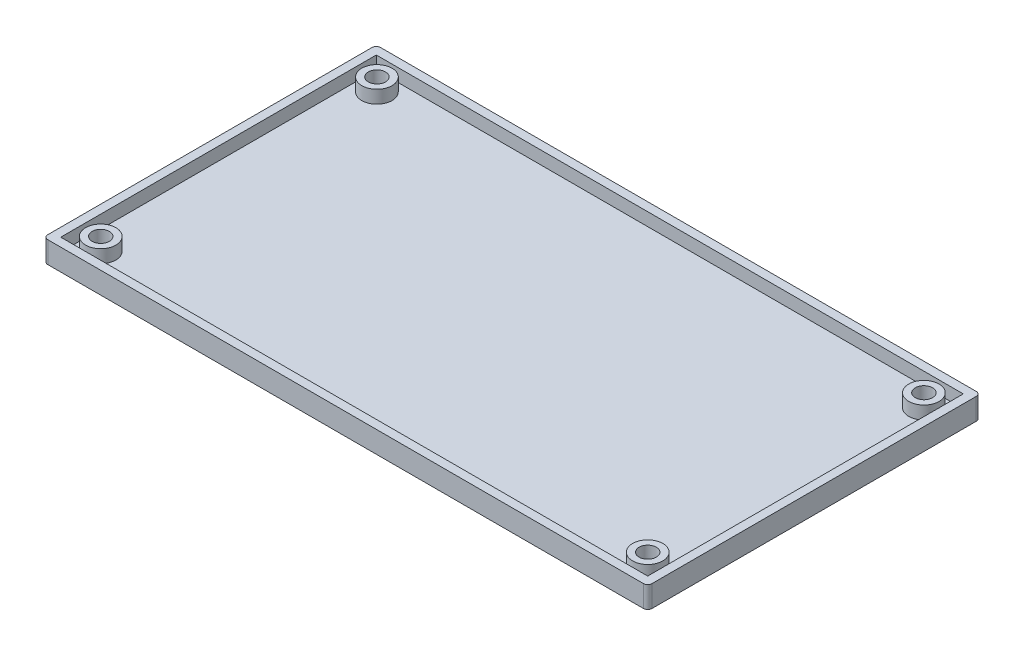
SolidWorks part; units mm, degrees
ref_plane "Front Plane" through (0, 0, 0) normal (0, 0, 1) x (1, 0, 0)
ref_plane "Top Plane" through (0, 0, 0) normal (0, 1, 0) x (1, 0, 0)
ref_plane "Right Plane" through (0, 0, 0) normal (1, 0, 0) x (0, 0, -1)
sketch "Sketch1" plane through (0, 0, 0) normal (0, 1, 0) x (1, 0, 0)
  line L0 (1.0429, 69.9365) -> (132.9972, 69.9365)
  line L1 (132.9972, 0.8484) -> (1.0429, 0.8484)
  line L2 (1.0429, 0.8484) -> (1.0429, 69.8095)
  line L3 (132.9972, 69.8095) -> (132.9972, 0.8484)
  line L4 (94.6421, 48.4741) -> (94.8961, 48.4741)
  line L5 (89.5621, 48.4741) -> (89.3081, 48.4741)
  line L6 (94.6421, 48.4741) -> (94.6421, 47.7121)
  line L7 (94.6421, 49.2361) -> (94.6421, 48.4741)
  line L8 (89.5621, 49.2361) -> (94.6421, 49.2361)
  line L9 (89.5621, 48.4741) -> (89.5621, 49.2361)
  line L10 (89.5621, 47.7121) -> (89.5621, 48.4741)
  line L11 (94.6421, 47.7121) -> (89.5621, 47.7121)
  line L12 (3.5161, 3.7303) -> (2.2461, 5.0003)
  line L13 (2.2461, 5.0003) -> (2.2461, 5.0145)
  line L14 (3.5161, 3.6429) -> (4.8731, 2.2859)
  line L15 (2.1446, 2.3221) -> (2.1953, 2.3221)
  line L16 (2.1953, 2.3221) -> (3.5161, 3.6429)
  line L17 (3.5161, 3.6429) -> (4.837, 4.9637)
  line L18 (4.837, 4.9637) -> (4.8878, 4.9637)
  line L19 (3.5161, 67.6973) -> (2.2461, 68.9673)
  line L20 (2.2461, 68.9673) -> (2.2461, 68.9814)
  line L21 (3.5161, 67.6099) -> (4.8731, 66.2529)
  line L22 (2.1446, 66.2891) -> (2.1953, 66.2891)
  line L23 (2.1953, 66.2891) -> (3.5161, 67.6099)
  line L24 (3.5161, 67.6099) -> (4.837, 68.9307)
  line L25 (4.837, 68.9307) -> (4.8878, 68.9307)
  line L26 (130.2022, 67.6975) -> (128.9322, 68.9675)
  line L27 (128.9322, 68.9675) -> (128.9322, 68.9817)
  line L28 (130.2022, 67.6101) -> (131.5591, 66.2532)
  line L29 (128.8306, 66.2893) -> (128.8814, 66.2893)
  line L30 (128.8814, 66.2893) -> (130.2022, 67.6101)
  line L31 (130.2022, 67.6101) -> (131.523, 68.9309)
  line L32 (131.523, 68.9309) -> (131.5738, 68.9309)
  line L33 (130.2022, 3.7303) -> (128.9322, 5.0003)
  line L34 (128.9322, 5.0003) -> (128.9322, 5.0145)
  line L35 (130.2022, 3.6429) -> (131.5591, 2.2859)
  line L36 (128.8306, 2.3221) -> (128.8814, 2.3221)
  line L37 (128.8814, 2.3221) -> (130.2022, 3.6429)
  line L38 (130.2022, 3.6429) -> (131.523, 4.9637)
  line L39 (131.523, 4.9637) -> (131.5738, 4.9637)
  line L40 (36.8771, 14.0372) -> (36.8771, 68.4373)
  line L41 (36.8771, 68.4373) -> (64.777, 68.4373)
  line L42 (64.777, 68.4373) -> (64.777, 14.0372)
  line L43 (64.777, 14.0372) -> (36.8771, 14.0372)
  line L44 (44.477, 62.8772) -> (44.477, 67.9572)
  line L45 (44.477, 67.9572) -> (45.747, 67.9572)
  line L46 (45.747, 67.9572) -> (45.747, 64.1472)
  line L47 (45.747, 64.1472) -> (47.017, 64.1472)
  line L48 (47.017, 64.1472) -> (47.017, 67.9572)
  line L49 (47.017, 67.9572) -> (48.287, 67.9572)
  line L50 (48.287, 67.9572) -> (48.287, 64.1472)
  line L51 (48.287, 64.1472) -> (49.557, 64.1472)
  line L52 (49.557, 64.1472) -> (49.557, 67.9572)
  line L53 (49.557, 67.9572) -> (50.827, 67.9572)
  line L54 (50.827, 67.9572) -> (50.827, 64.1472)
  line L55 (50.827, 64.1472) -> (52.097, 64.1472)
  line L56 (52.097, 64.1472) -> (52.097, 67.9572)
  line L57 (52.097, 67.9572) -> (53.367, 67.9572)
  line L58 (53.367, 67.9572) -> (53.367, 64.1472)
  line L59 (53.367, 64.1472) -> (54.637, 64.1472)
  line L60 (54.637, 64.1472) -> (54.637, 67.9572)
  line L61 (54.637, 67.9572) -> (55.907, 67.9572)
  line L62 (55.907, 67.9572) -> (55.907, 64.1472)
  line L63 (55.907, 64.1472) -> (58.447, 64.1472)
  line L64 (64.7971, 62.3171) -> (36.857, 62.3171)
  line L65 (36.857, 62.3171) -> (39.397, 62.3171)
  line L66 (39.397, 62.3171) -> (39.397, 13.911)
  line L67 (39.397, 13.911) -> (36.857, 13.911)
  line L68 (36.857, 13.911) -> (36.857, 62.3171)
  line L69 (62.257, 62.3171) -> (64.7971, 62.3171)
  line L70 (64.7971, 62.3171) -> (64.7971, 13.911)
  line L71 (64.7971, 13.911) -> (62.257, 13.911)
  line L72 (62.257, 13.911) -> (62.257, 62.3171)
  line L73 (110.4206, 7.58) -> (110.426, 10.1279)
  line L74 (110.2936, 13.93) -> (110.299, 16.4779)
  line L75 (73.1791, 8.342) -> (72.9251, 8.342)
  line L76 (78.2591, 8.342) -> (78.5131, 8.342)
  line L77 (73.1791, 8.342) -> (73.1791, 9.104)
  line L78 (73.1791, 7.58) -> (73.1791, 8.342)
  line L79 (78.2591, 7.58) -> (73.1791, 7.58)
  line L80 (78.2591, 8.342) -> (78.2591, 7.58)
  line L81 (78.2591, 9.104) -> (78.2591, 8.342)
  line L82 (73.1791, 9.104) -> (78.2591, 9.104)
  line L83 (118.7722, 25.233) -> (118.7722, 24.979)
  line L84 (118.7722, 30.3131) -> (118.7722, 30.5671)
  line L85 (118.7722, 25.233) -> (118.0102, 25.233)
  line L86 (119.5342, 25.233) -> (118.7722, 25.233)
  line L87 (119.5342, 30.3131) -> (119.5342, 25.233)
  line L88 (118.7722, 30.3131) -> (119.5342, 30.3131)
  line L89 (118.0102, 30.3131) -> (118.7722, 30.3131)
  line L90 (118.0102, 25.233) -> (118.0102, 30.3131)
  line L91 (75.7191, 48.7281) -> (75.9731, 48.7281)
  line L92 (70.6391, 48.7281) -> (70.3851, 48.7281)
  line L93 (75.7191, 48.7281) -> (75.7191, 47.9661)
  line L94 (75.7191, 49.4901) -> (75.7191, 48.7281)
  line L95 (70.6391, 49.4901) -> (75.7191, 49.4901)
  line L96 (70.6391, 48.7281) -> (70.6391, 49.4901)
  line L97 (70.6391, 47.9661) -> (70.6391, 48.7281)
  line L98 (75.7191, 47.9661) -> (70.6391, 47.9661)
  line L99 (127.9162, 32.5991) -> (127.9162, 32.3451)
  line L100 (127.9162, 37.6791) -> (127.9162, 37.9331)
  line L101 (127.9162, 32.5991) -> (127.1542, 32.5991)
  line L102 (128.6782, 32.5991) -> (127.9162, 32.5991)
  line L103 (128.6782, 37.6791) -> (128.6782, 32.5991)
  line L104 (127.9162, 37.6791) -> (128.6782, 37.6791)
  line L105 (127.1542, 37.6791) -> (127.9162, 37.6791)
  line L106 (127.1542, 32.5991) -> (127.1542, 37.6791)
  line L107 (102.2621, 8.723) -> (102.5161, 8.723)
  line L108 (97.1821, 8.723) -> (96.9281, 8.723)
  line L109 (102.2621, 8.723) -> (102.2621, 7.961)
  line L110 (102.2621, 9.485) -> (102.2621, 8.723)
  line L111 (97.1821, 9.485) -> (102.2621, 9.485)
  line L112 (97.1821, 8.723) -> (97.1821, 9.485)
  line L113 (97.1821, 7.961) -> (97.1821, 8.723)
  line L114 (102.2621, 7.961) -> (97.1821, 7.961)
  line L115 (102.2621, 14.946) -> (102.5161, 14.946)
  line L116 (97.1821, 14.946) -> (96.9281, 14.946)
  line L117 (102.2621, 14.946) -> (102.2621, 14.184)
  line L118 (102.2621, 15.708) -> (102.2621, 14.946)
  line L119 (97.1821, 15.708) -> (102.2621, 15.708)
  line L120 (97.1821, 14.946) -> (97.1821, 15.708)
  line L121 (97.1821, 14.184) -> (97.1821, 14.946)
  line L122 (102.2621, 14.184) -> (97.1821, 14.184)
  line L123 (88.4691, 65.5692) -> (101.0691, 65.5692)
  line L124 (88.4691, 52.9693) -> (101.0691, 52.9692)
  line L125 (88.4691, 65.5692) -> (88.4691, 63.2895)
  line L126 (88.4691, 60.329) -> (88.4691, 58.2095)
  line L127 (88.4691, 55.2489) -> (88.4691, 52.9693)
  line L128 (101.0691, 65.5692) -> (101.0691, 63.2895)
  line L129 (101.0691, 60.329) -> (101.0691, 58.2095)
  line L130 (101.0691, 55.2489) -> (101.0691, 52.9692)
  line L131 (69.5461, 65.6962) -> (82.1461, 65.6962)
  line L132 (69.5461, 53.0963) -> (82.1461, 53.0962)
  line L133 (69.5461, 65.6962) -> (69.5461, 63.4165)
  line L134 (69.5461, 60.456) -> (69.5461, 58.3365)
  line L135 (69.5461, 55.3759) -> (69.5461, 53.0963)
  line L136 (82.1461, 65.6962) -> (82.1461, 63.4165)
  line L137 (82.1461, 60.456) -> (82.1461, 58.3365)
  line L138 (82.1461, 55.3759) -> (82.1461, 53.0962)
  line L139 (91.2842, 17.3184) -> (85.4438, 17.3184)
  line L140 (85.4438, 17.3184) -> (85.4345, 17.309)
  line L141 (85.4345, 17.309) -> (85.4345, 4.709)
  line L142 (85.4345, 4.709) -> (91.2842, 4.709)
  line L143 (91.2842, 14.184) -> (89.6891, 14.184)
  line L144 (89.6891, 14.184) -> (89.6891, 12.914)
  line L145 (89.6891, 12.914) -> (91.2842, 12.914)
  line L146 (91.2842, 11.644) -> (89.6891, 11.644)
  line L147 (89.6891, 11.644) -> (89.6891, 10.374)
  line L148 (89.6891, 10.374) -> (91.2842, 10.374)
  line L149 (91.2842, 9.104) -> (89.6891, 9.104)
  line L150 (89.6891, 9.104) -> (89.6891, 7.834)
  line L151 (89.6891, 7.834) -> (91.2842, 7.834)
  line L152 (91.2842, 4.6996) -> (91.2842, 14.819)
  line L153 (91.2842, 14.819) -> (91.2842, 17.3184)
  line L154 (5.2238, 61.9788) -> (32.4221, 61.9788)
  line L155 (32.4221, 61.9788) -> (32.4221, 34.1784)
  line L156 (32.4221, 34.1784) -> (25.3228, 34.1784)
  line L157 (25.3228, 34.1784) -> (25.3228, 37.93)
  line L158 (25.3228, 37.93) -> (12.4729, 37.93)
  line L159 (12.4729, 37.93) -> (12.4729, 34.1784)
  line L160 (12.4729, 34.1784) -> (5.2238, 34.1784)
  line L161 (5.2238, 34.1784) -> (5.2238, 61.9788)
  line L162 (111.2791, 59.3188) -> (111.2791, 60.5611)
  line L163 (111.2791, 60.5611) -> (123.4712, 60.5611)
  line L164 (123.4712, 60.5611) -> (123.4712, 59.3188)
  line L165 (123.4712, 48.0035) -> (123.4712, 44.9611)
  line L166 (123.4712, 44.9611) -> (117.8621, 44.9611)
  line L167 (116.8882, 44.9611) -> (111.2791, 44.9611)
  line L168 (111.2791, 44.9611) -> (111.2791, 48.0035)
  line L169 (123.4712, 58.2035) -> (123.4712, 49.1189)
  line L170 (111.2791, 49.1189) -> (111.2791, 58.2035)
  line L171 (115.5972, 69.8811) -> (115.5972, 69.1831)
  line L172 (115.5972, 69.1831) -> (117.8539, 69.1831)
  line L173 (117.8539, 69.1831) -> (117.8539, 69.8811)
  line L174 (112.3512, 69.8811) -> (112.3512, 69.1831)
  line L175 (112.3512, 69.1831) -> (114.6079, 69.1831)
  line L176 (114.6079, 69.1831) -> (114.6079, 69.8811)
  line L177 (118.8992, 69.8811) -> (118.8992, 69.1831)
  line L178 (118.8992, 69.1831) -> (121.1559, 69.1831)
  line L179 (121.1559, 69.1831) -> (121.1559, 69.8811)
  line L180 (111.5331, 68.5401) -> (121.8202, 68.5401)
  line L181 (111.5331, 64.2221) -> (121.8202, 64.2221)
  line L182 (111.5331, 63.3331) -> (121.8202, 63.3331)
  line L183 (111.4901, 69.9082) -> (121.9902, 69.9082)
  line L184 (121.9902, 69.9082) -> (121.9902, 62.5081)
  line L185 (121.9902, 62.5081) -> (111.4901, 62.5081)
  line L186 (111.4901, 62.5081) -> (111.4901, 69.9082)
  line L187 (72.4171, 40.7271) -> (104.9291, 40.7271)
  line L188 (104.9291, 40.7271) -> (104.9291, 20.407)
  line L189 (104.9291, 20.407) -> (72.4171, 20.407)
  line L190 (72.4171, 20.407) -> (72.4171, 40.7271)
  line L191 (72.7981, 28.6621) -> (72.7981, 29.9321)
  line L192 (72.7981, 29.9321) -> (73.4331, 30.5671)
  line L193 (73.4331, 30.5671) -> (72.7981, 31.2021)
  line L194 (72.7981, 31.2021) -> (72.7981, 32.4721)
  line L195 (72.7981, 32.4721) -> (73.4331, 33.1071)
  line L196 (73.4331, 33.1071) -> (72.7981, 33.7421)
  line L197 (72.7981, 33.7421) -> (72.7981, 35.0121)
  line L198 (72.7981, 35.0121) -> (73.4331, 35.6471)
  line L199 (73.4331, 35.6471) -> (74.7031, 35.6471)
  line L200 (74.7031, 35.6471) -> (75.3381, 35.0121)
  line L201 (75.3381, 35.0121) -> (75.3381, 33.7421)
  line L202 (75.3381, 33.7421) -> (74.7031, 33.1071)
  line L203 (74.7031, 33.1071) -> (75.3381, 32.4721)
  line L204 (75.3381, 32.4721) -> (75.3381, 31.2021)
  line L205 (75.3381, 31.2021) -> (74.7031, 30.5671)
  line L206 (74.7031, 30.5671) -> (75.3381, 29.9321)
  line L207 (75.3381, 29.9321) -> (75.3381, 28.6621)
  line L208 (75.3381, 28.6621) -> (74.7031, 28.0271)
  line L209 (74.7031, 28.0271) -> (75.3381, 27.392)
  line L210 (75.3381, 27.392) -> (75.3381, 26.122)
  line L211 (75.3381, 26.122) -> (74.7031, 25.487)
  line L212 (74.7031, 25.487) -> (73.4331, 25.487)
  line L213 (73.4331, 25.487) -> (72.7981, 26.122)
  line L214 (72.7981, 26.122) -> (72.7981, 27.392)
  line L215 (72.7981, 27.392) -> (73.4331, 28.0271)
  line L216 (73.4331, 28.0271) -> (72.7981, 28.6621)
  line L217 (121.3792, 19.013) -> (126.5792, 19.013)
  line L218 (126.5792, 19.013) -> (126.5792, 16.213)
  line L219 (121.3792, 16.213) -> (126.5792, 16.213)
  line L220 (121.3792, 19.013) -> (121.3792, 16.213)
  line L221 (122.3384, 19.013) -> (122.3384, 16.213)
  line L222 (114.9022, 44.0321) -> (120.1022, 44.0321)
  line L223 (120.1022, 44.0321) -> (120.1022, 41.2321)
  line L224 (114.9022, 41.2321) -> (120.1022, 41.2321)
  line L225 (114.9022, 44.0321) -> (114.9022, 41.2321)
  line L226 (115.8614, 44.0321) -> (115.8614, 41.2321)
  line L227 (128.8801, 25.1329) -> (124.9203, 25.1329)
  line L228 (120.7521, 33.6419) -> (116.7923, 33.6419)
  line L229 (73.5575, 20.0235) -> (68.4775, 20.0235)
  line L230 (68.4775, 20.0235) -> (68.4775, 17.4835)
  line L231 (68.4775, 17.4835) -> (73.5575, 17.4835)
  line L232 (73.5575, 17.4835) -> (73.5575, 20.0235)
  line L233 (92.1024, 47.2041) -> (90.1378, 47.2041) construction
  line L234 (50.573, 20.661) -> (50.573, 51.2046) construction
  line L235 (53.394, 33.0669) -> (53.394, 42.9729) construction
  line L236 (106.4531, 8.596) -> (106.4531, 12.4536) construction
  line L237 (106.3261, 14.946) -> (106.3261, 18.8037) construction
  line L238 (117.5022, 27.7731) -> (117.5022, 29.7376) construction
  line L239 (73.1793, 47.4581) -> (71.2148, 47.4581) construction
  line L240 (126.6464, 35.1391) -> (126.6464, 37.1036) construction
  line L241 (100.8651, 7.072) -> (98.9006, 7.072) construction
  line L242 (99.7221, 13.676) -> (97.7576, 13.676) construction
  line L243 (84.8555, 10.8896) -> (84.8555, 12.8542) construction
  line L244 (110.8981, 52.625) -> (110.8981, 54.5895) construction
  arc A0 (5.4161, 3.6429) -> (5.4161, 3.6382) centre (3.5162, 3.6406) ccw
  arc A1 (5.4161, 67.6099) -> (5.4161, 67.6052) centre (3.5162, 67.6075) ccw
  arc A2 (132.1021, 67.6101) -> (132.1021, 67.6055) centre (130.2022, 67.6078) ccw
  arc A3 (132.1021, 3.6429) -> (132.1021, 3.6382) centre (130.2022, 3.6406) ccw
  arc A4 (125.5026, 9.612) -> (125.5014, 9.485) centre (118.3906, 9.6125) ccw
  arc A5 (119.9146, 9.104) -> (119.8274, 8.8936) centre (118.3905, 9.612) ccw
  arc A6 (110.4206, 10.1154) -> (110.4206, 7.58) centre (108.8737, 8.8477) ccw
  arc A7 (110.2936, 16.4655) -> (110.2936, 13.93) centre (108.7467, 15.1977) ccw
  arc A8 (128.8814, 25.1316) -> (124.919, 25.1316) centre (126.9002, 26.63) ccw
  arc A9 (120.7534, 33.6407) -> (116.791, 33.6407) centre (118.7722, 35.1391) ccw
  circle A10 centre (94.7671, 59.2706) radius 4.4981
  circle A11 centre (94.7691, 59.2691) radius 4.064
  circle A12 centre (75.844, 59.3976) radius 4.4981
  circle A13 centre (75.8461, 59.3961) radius 4.064
  circle A14 centre (92.4831, 30.5671) radius 9.779
  text T0 "R3" font "ARIAL" height 1.143
  text T1 "SCREW1" font "ARIAL" height 1.143
  text T2 "SCREW2" font "ARIAL" height 1.143
  text T3 "SCREW3" font "ARIAL" height 1.143
  text T4 "SCREW4" font "ARIAL" height 1.143
  text T5 "BUZ1" font "ARIAL" height 1.143
  text T6 "H1" font "ARIAL" height 1.143
  text T7 "ESP-WROOM-32 38 PIN" font "ARIAL" height 2.032
  text T8 "DEVKIT" font "ARIAL" height 2.032
  text T9 "LED2" font "ARIAL" height 1.143
  text T10 "LED3" font "ARIAL" height 1.143
  text T11 "R1" font "ARIAL" height 1.143
  text T12 "R2" font "ARIAL" height 1.143
  text T13 "R4" font "ARIAL" height 1.143
  text T14 "R5" font "ARIAL" height 1.143
  text T15 "R6" font "ARIAL" height 1.143
  text T16 "R7" font "ARIAL" height 1.143
  text T17 "SW2" font "ARIAL" height 1.143
  text T18 "SW3" font "ARIAL" height 1.143
  text T19 "U1" font "ARIAL" height 1.143
  text T20 "U3" font "ARIAL" height 1.143
  text T21 "U4" font "ARIAL" height 1.143
  text T22 "U5" font "ARIAL" height 1.143
  text T23 "&#96;SENSOR" font "ARIAL" height 1.27
  text T24 "U6" font "ARIAL" height 1.143
  text T25 "D3" font "ARIAL" height 1.143
  text T26 "D9" font "ARIAL" height 1.143
  text T27 "Q1" font "ARIAL" height 1.143
  text T28 "Q5" font "ARIAL" height 1.143
  text T29 "C6" font "ARIAL" height 1.143
sketch "Sketch2" plane through (0, 0, 0) normal (0, 1, 0) x (1, 0, 0)
  line L0 (-2.9571, 73.9365) -> (-2.9571, -3.1516)
  line L1 (1.0429, 69.9365) -> (132.9972, 69.9365) construction
  line L2 (1.0429, 69.9365) -> (1.0429, 0.8484) construction
  line L3 (1.0429, 0.8484) -> (132.9972, 0.8484) construction
  line L4 (132.9972, 69.9365) -> (132.9972, 0.8484) construction
  line L5 (-2.9571, -3.1516) -> (136.9972, -3.1516)
  line L6 (136.9972, 73.9365) -> (136.9972, -3.1516)
  line L7 (-2.9571, 73.9365) -> (136.9972, 73.9365)
  dimension "D1" = 4
extrude "Boss-Extrude1" add sketch "Sketch2" along normal blind 2
sketch "Sketch3" plane through (0, 2, 0) normal (0, 1, 0) x (1, 0, 0)
  line L0 (-0.9571, 71.9365) -> (-0.9571, -1.1516)
  line L1 (-2.9571, 73.9365) -> (136.9972, 73.9365)
  line L2 (-2.9571, 73.9365) -> (-2.9571, -3.1516)
  line L3 (-2.9571, -3.1516) -> (136.9972, -3.1516)
  line L4 (136.9972, 73.9365) -> (136.9972, -3.1516)
  line L5 (-0.9571, -1.1516) -> (134.9972, -1.1516)
  line L6 (134.9972, 71.9365) -> (134.9972, -1.1516)
  line L7 (-0.9571, 71.9365) -> (134.9972, 71.9365)
  circle A0 centre (3.5161, 67.6099) radius 3.5
  circle A1 centre (130.2022, 67.6101) radius 3.5
  circle A2 centre (130.2022, 3.6429) radius 3.5
  circle A3 centre (3.5161, 3.6429) radius 3.5
  line M10 (136.9972, 73.9365) -> (-2.9571, 73.9365)
  line M11 (-2.9571, 73.9365) -> (-2.9571, -3.1516)
  line M12 (-2.9571, -3.1516) -> (136.9972, -3.1516)
  line M13 (136.9972, -3.1516) -> (136.9972, 73.9365)
  dimension "D2" = 7
  dimension "D1" = 2
extrude "Boss-Extrude2" add sketch "Sketch3" along normal blind 3 contours A3 | L0 L7 L6 L5 M13 M10 M11 M12 | A0 | A1 | A2
sketch "Sketch4" plane through (0, 5, 0) normal (0, 1, 0) x (1, 0, 0)
  circle A0 centre (3.5161, 67.6099) radius 2
  circle A1 centre (130.2022, 67.6101) radius 2
  circle A2 centre (130.2022, 3.6429) radius 2
  circle A3 centre (3.5161, 3.6429) radius 2
  dimension "D1" = 4
extrude "Cut-Extrude1" cut sketch "Sketch4" against normal blind 9
fillet "Fillet1" radius 1 4 edges at (-2.9571, 2.5, -73.9365) (136.9972, 2.5, -73.9365) (136.9972, 2.5, 3.1516) (-2.9571, 2.5, 3.1516)
